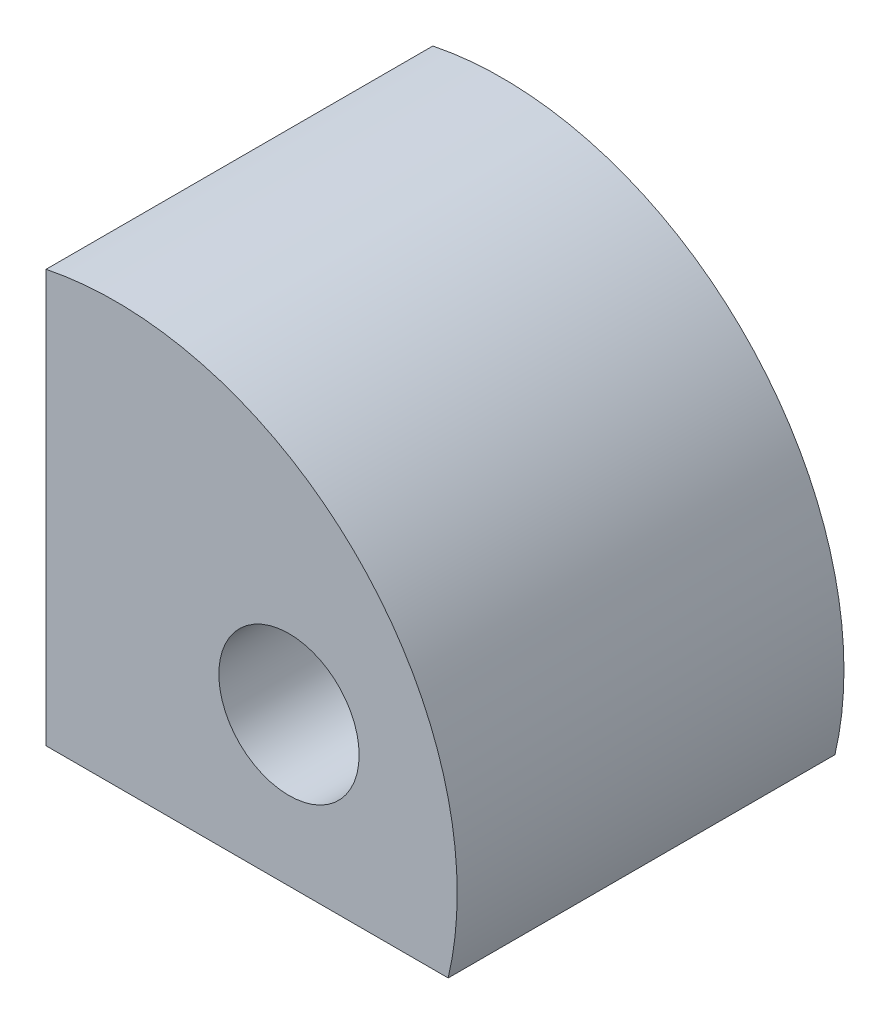
SolidWorks part; units mm, degrees
ref_plane "Front Plane" through (0, 0, 0) normal (0, 0, 1) x (1, 0, 0)
ref_plane "Top Plane" through (0, 0, 0) normal (0, 1, 0) x (1, 0, 0)
ref_plane "Right Plane" through (0, 0, 0) normal (1, 0, 0) x (0, 0, -1)
sketch "Sketch1" plane through (0, 0, 0) normal (0, 0, 1) x (1, 0, 0)
  line L22 (6.8525, -4.749) -> (-2.8942, -4.749)
  line L23 (-2.8942, 5.2522) -> (-2.8942, -4.749)
  circle A8 centre (2.9937, -1.149) radius 1.7
  arc A11 (6.8525, -4.749) -> (-2.8942, 5.2522) centre (-1.2151, -2.8614) ccw
  dimension "D2" = 9.7467
  dimension "D3" = 3.4
  dimension "D4" = 3.8588
  dimension "D1" = 3.6
  dimension "D6" = 3.8588
  dimension "D5" = 10.0012
extrude "Boss-Extrude1" add sketch "Sketch1" along normal blind 9.3733
